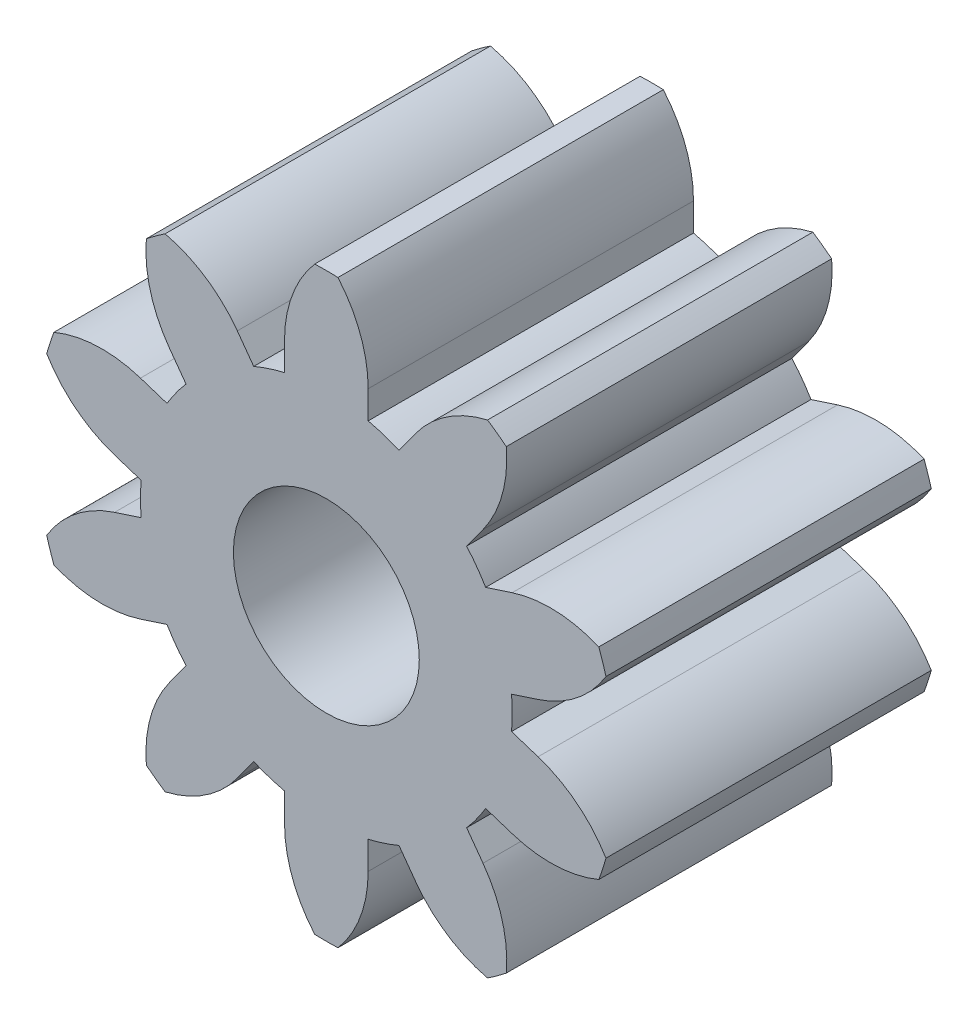
SolidWorks part; units mm, degrees
ref_plane "Plano frontal" through (0, 0, 0) normal (0, 0, 1) x (1, 0, 0)
ref_plane "Plano superior" through (0, 0, 0) normal (0, 1, 0) x (1, 0, 0)
ref_plane "Plano direito" through (0, 0, 0) normal (1, 0, 0) x (0, 0, -1)
sketch "Esboço1" plane through (0, 0, 0) normal (0, 0, 1) x (1, 0, 0)
  line L0 (0, 0) -> (0, -3.125) construction
  line L1 (-0.125, -3.1225) -> (0.125, -3.1225) construction
  line L2 (-0.45, -2.2487) -> (-0.45, -1.9487)
  line L3 (0.45, -2.2487) -> (0.45, -1.9487)
  line L4 (-1.6858, -1.5547) -> (-1.5095, -1.312)
  line L5 (-0.45, -2.2487) -> (0.45, -2.2487) construction
  line L6 (-0.9577, -2.0838) -> (-0.7814, -1.841)
  line L7 (-2.2777, -0.2669) -> (-1.9924, -0.1742)
  line L8 (-1.9996, -1.1229) -> (-1.7143, -1.0302)
  line L9 (-1.9996, 1.1229) -> (-1.7143, 1.0302)
  line L10 (-2.2777, 0.2669) -> (-1.9924, 0.1742)
  line L11 (-0.9577, 2.0838) -> (-0.7814, 1.841)
  line L12 (-1.6858, 1.5547) -> (-1.5095, 1.312)
  line L13 (0.45, 2.2487) -> (0.45, 1.9487)
  line L14 (-0.45, 2.2487) -> (-0.45, 1.9487)
  line L15 (1.6858, 1.5547) -> (1.5095, 1.312)
  line L16 (0.9577, 2.0838) -> (0.7814, 1.841)
  line L17 (2.2777, 0.2669) -> (1.9924, 0.1742)
  line L18 (1.9996, 1.1229) -> (1.7143, 1.0302)
  line L19 (1.9996, -1.1229) -> (1.7143, -1.0302)
  line L20 (2.2777, -0.2669) -> (1.9924, -0.1742)
  line L21 (0.9577, -2.0838) -> (0.7814, -1.841)
  line L22 (1.6858, -1.5547) -> (1.5095, -1.312)
  line L23 (-0.45, -1.9487) -> (0.45, -1.9487) construction
  circle A0 centre (0, 0) radius 3.125 construction
  circle A1 centre (0, 0) radius 2
  arc A2 (-0.125, -3.1225) -> (0.125, -3.1225) centre (0, 0) ccw
  circle A3 centre (0, 0) radius 2.2933 construction
  arc A4 (-0.45, -2.2487) -> (-0.125, -3.1225) centre (0.8871, -2.2487) ccw
  arc A5 (-1.6858, -1.5547) -> (-1.9365, -2.4527) centre (-0.6041, -2.3407) ccw
  arc A6 (0.125, -3.1225) -> (0.45, -2.2487) centre (-0.8871, -2.2487) ccw
  arc A7 (-1.9365, -2.4527) -> (-1.7342, -2.5996) centre (0, 0) ccw
  arc A8 (-1.7342, -2.5996) -> (-0.9577, -2.0838) centre (-2.0394, -1.2978) ccw
  arc A9 (-2.2777, -0.2669) -> (-3.0083, -0.846) centre (-1.8645, -1.5386) ccw
  arc A10 (-3.0083, -0.846) -> (-2.931, -1.0838) centre (0, 0) ccw
  arc A11 (-2.931, -1.0838) -> (-1.9996, -1.1229) centre (-2.4128, 0.1488) ccw
  arc A12 (-1.9996, 1.1229) -> (-2.931, 1.0838) centre (-2.4128, -0.1488) ccw
  arc A13 (-2.931, 1.0838) -> (-3.0083, 0.846) centre (0, 0) ccw
  arc A14 (-3.0083, 0.846) -> (-2.2777, 0.2669) centre (-1.8645, 1.5386) ccw
  arc A15 (-0.9577, 2.0838) -> (-1.7342, 2.5996) centre (-2.0394, 1.2978) ccw
  arc A16 (-1.7342, 2.5996) -> (-1.9365, 2.4527) centre (0, 0) ccw
  arc A17 (-1.9365, 2.4527) -> (-1.6858, 1.5547) centre (-0.6041, 2.3407) ccw
  arc A18 (0.45, 2.2487) -> (0.125, 3.1225) centre (-0.8871, 2.2487) ccw
  arc A19 (0.125, 3.1225) -> (-0.125, 3.1225) centre (0, 0) ccw
  arc A20 (-0.125, 3.1225) -> (-0.45, 2.2487) centre (0.8871, 2.2487) ccw
  arc A21 (1.6858, 1.5547) -> (1.9365, 2.4527) centre (0.6041, 2.3407) ccw
  arc A22 (1.9365, 2.4527) -> (1.7342, 2.5996) centre (0, 0) ccw
  arc A23 (1.7342, 2.5996) -> (0.9577, 2.0838) centre (2.0394, 1.2978) ccw
  arc A24 (2.2777, 0.2669) -> (3.0083, 0.846) centre (1.8645, 1.5386) ccw
  arc A25 (3.0083, 0.846) -> (2.931, 1.0838) centre (0, 0) ccw
  arc A26 (2.931, 1.0838) -> (1.9996, 1.1229) centre (2.4128, -0.1488) ccw
  arc A27 (1.9996, -1.1229) -> (2.931, -1.0838) centre (2.4128, 0.1488) ccw
  arc A28 (2.931, -1.0838) -> (3.0083, -0.846) centre (0, 0) ccw
  arc A29 (3.0083, -0.846) -> (2.2777, -0.2669) centre (1.8645, -1.5386) ccw
  arc A30 (0.9577, -2.0838) -> (1.7342, -2.5996) centre (2.0394, -1.2978) ccw
  arc A31 (1.7342, -2.5996) -> (1.9365, -2.4527) centre (0, 0) ccw
  arc A32 (1.9365, -2.4527) -> (1.6858, -1.5547) centre (0.6041, -2.3407) ccw
  point P89 (0, 0)
  dimension "D1" = 6.25
  dimension "D2" = 4
  dimension "D3" = 0.25
  dimension "D5" = 0.9
  dimension "D6" = 0.3
  dimension "D4" = 10
extrude "Ressalto-extrusão1" add sketch "Esboço1" along normal blind 3.5 contours A1 | A10 A11 L8 A1 L7 A9 | A13 A14 L10 A1 L9 A12 | A16 A17 L12 A1 L11 A15 | A19 A20 L14 A1 L13 A18 | A22 A23 L16 A1 L15 A21 | A25 A26 L18 A1 L17 A24 | A28 A29 L20 A1 L19 A27 | A31 A32 L22 A1 L21 A30 | A2 A6 L3 A1 L2 A4 | A7 A8 L6 A1 L4 A5
sketch "Esboço2" plane through (0, 0, 3.5) normal (0, 0, 1) x (1, 0, 0)
  circle A0 centre (0, 0) radius 1
  dimension "D1" = 2
extrude "Corte-extrusão1" cut sketch "Esboço2" against normal up to next
